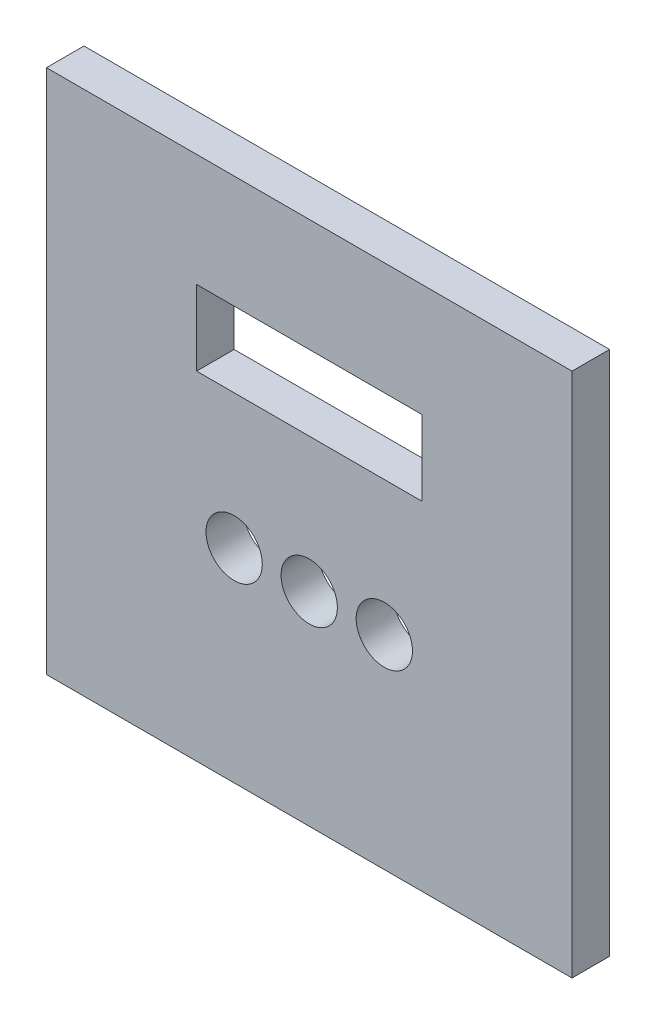
SolidWorks part; units mm, degrees
ref_plane "Front Plane" through (0, 0, 0) normal (0, 0, 1) x (1, 0, 0)
ref_plane "Top Plane" through (0, 0, 0) normal (0, 1, 0) x (1, 0, 0)
ref_plane "Right Plane" through (0, 0, 0) normal (1, 0, 0) x (0, 0, -1)
sketch "Sketch1" plane through (0, 0, 0) normal (0, 0, 1) x (1, 0, 0)
  line L1 (-70, 70) -> (70, 70)
  line L2 (-70, 70) -> (-70, -70)
  line L3 (-70, -70) -> (70, -70)
  line L4 (70, 70) -> (70, -70)
  line L5 (-70, 70) -> (70, -70) construction
  line L6 (-70, -70) -> (70, 70) construction
  point P0 (0, 0)
  dimension "D1" = 140
extrude "Boss-Extrude1" add sketch "Sketch1" along normal blind 10
sketch "Sketch2" plane through (0, 0, 10) normal (0, 0, 1) x (1, 0, 0)
  line L0 (-70, 70) -> (70, 70) construction
  line L1 (-30, 40) -> (30, 40)
  line L2 (-30, 40) -> (-30, 20)
  line L3 (-30, 20) -> (30, 20)
  line L4 (30, 40) -> (30, 20)
  line L5 (-30, 40) -> (30, 20) construction
  line L6 (-30, 20) -> (30, 40) construction
  point P0 (0, 30)
  point P9 (0, 70)
  dimension "D1" = 60
  dimension "D2" = 20
  dimension "D3" = 30
extrude "Cut-Extrude2" cut sketch "Sketch2" against normal through all
sketch "Sketch3" plane through (0, 0, 10) normal (0, 0, 1) x (1, 0, 0)
  circle A0 centre (-20, -15.8237) radius 7.5
  circle A1 centre (0, -15.8237) radius 7.5
  circle A2 centre (20, -15.8237) radius 7.5
  point P2 (0, 0)
  dimension "D1" = 15
  dimension "D2" = 3
extrude "Cut-Extrude3" cut sketch "Sketch3" against normal through all
